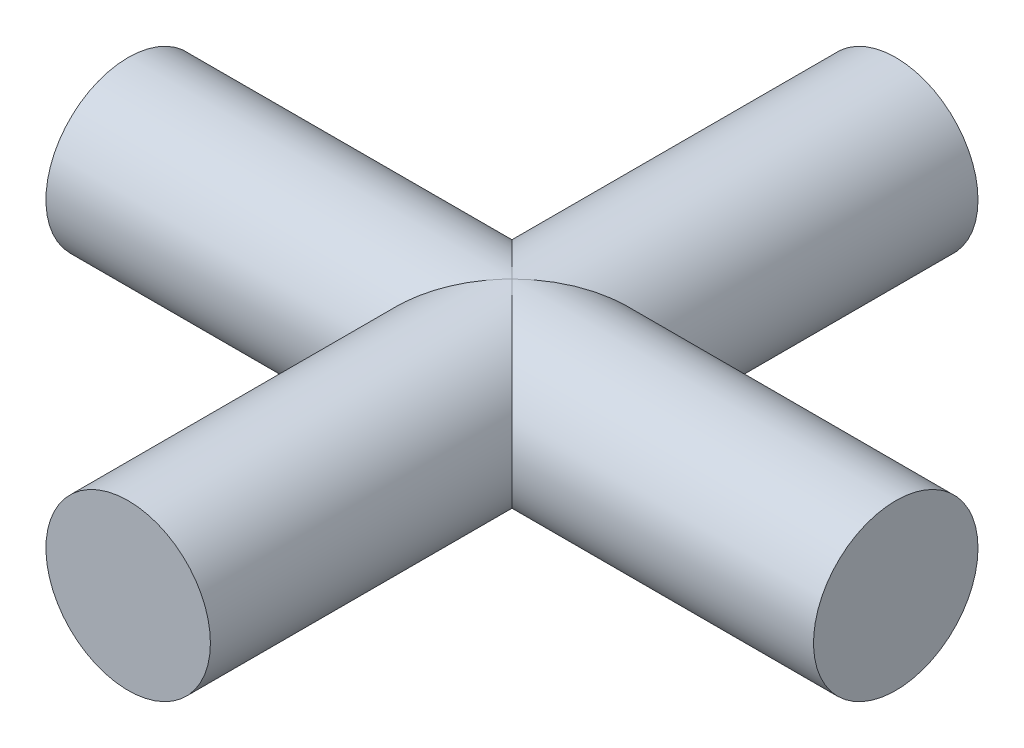
SolidWorks part; units mm, degrees
ref_plane "前视基准面" through (0, 0, 0) normal (0, 0, 1) x (1, 0, 0)
ref_plane "上视基准面" through (0, 0, 0) normal (0, 1, 0) x (1, 0, 0)
ref_plane "右视基准面" through (0, 0, 0) normal (1, 0, 0) x (0, 0, -1)
other "Configuration Table"
sketch "草图1" plane through (0, 0, 0) normal (1, 0, 0) x (0, 0, -1)
  circle A0 centre (0, 0) radius 1.5
  dimension "D1" = 3
extrude "凸台-拉伸1" add sketch "草图1" along normal blind 14
sketch "草图2" plane through (0, 0, 0) normal (0, 0, 1) x (1, 0, 0)
  circle A0 centre (7, 0) radius 1.5
  dimension "D1" = 7
  dimension "D2" = 3
extrude "凸台-拉伸2" add sketch "草图2" along normal mid plane 14
